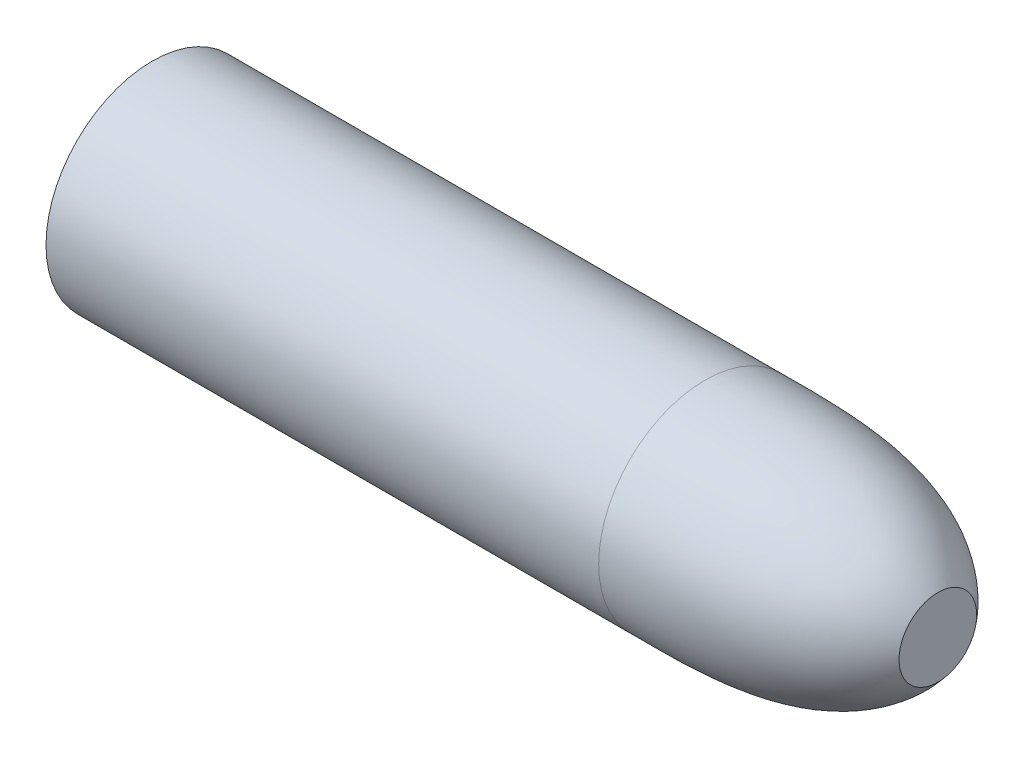
SolidWorks part; units mm, degrees
ref_plane "Front Plane" through (0, 0, 0) normal (0, 0, 1) x (1, 0, 0)
ref_plane "Top Plane" through (0, 0, 0) normal (0, 1, 0) x (1, 0, 0)
ref_plane "Right Plane" through (0, 0, 0) normal (1, 0, 0) x (0, 0, -1)
sketch "Sketch1" plane through (0, 0, 0) normal (0, 0, 1) x (1, 0, 0)
  line L0 (0, 0) -> (257, 0) construction
  line L2 (0, 0) -> (0, 34.75)
  line L3 (0, 34.75) -> (180.8, 34.75)
  line L5 (257, 0) -> (257, 12.7)
  line L6 (0, 0) -> (257, 0)
  spline S0 degree 3 poles (180.8, 34.75) (206.6269, 34.8833) (239.0153, 35.3923) (257, 12.7) knots 0 0 0 0 1 1 1 1
  dimension "D5" = 211.8665
  dimension "D1" = 257
  dimension "D2" = 34.75
  dimension "D3" = 180.8
  dimension "D4" = 12.7
  dimension "D6" = 240.1133
  dimension "D7" = 26.2635
  dimension "D8" = 33.7783
revolve "Revolve3" add sketch "Sketch1" angle 360 about L0
